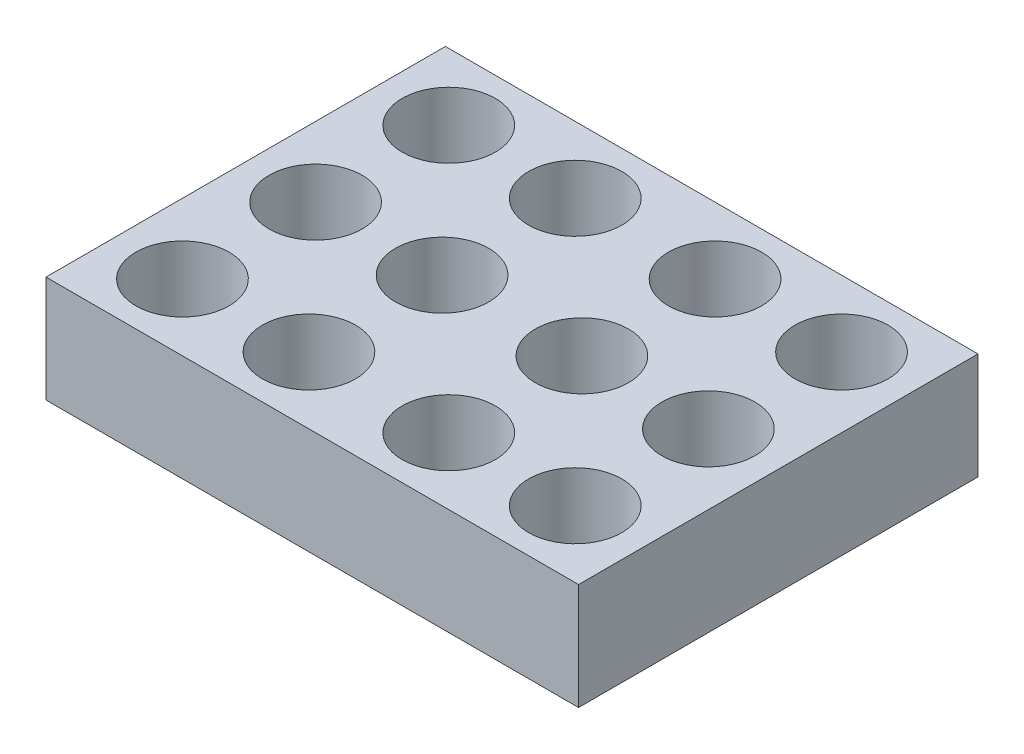
SolidWorks part; units mm, degrees
material "Polietileno reticulado"
ref_plane "Alzado" through (0, 0, 0) normal (0, 0, 1) x (1, 0, 0)
ref_plane "Planta" through (0, 0, 0) normal (0, 1, 0) x (1, 0, 0)
ref_plane "Vista lateral" through (0, 0, 0) normal (1, 0, 0) x (0, 0, -1)
sketch "Croquis1" plane through (0, 0, 0) normal (0, 1, 0) x (1, 0, 0)
  line L1 (-200, -150) -> (200, -150)
  line L2 (-200, -150) -> (-200, 150)
  line L3 (-200, 150) -> (200, 150)
  line L4 (200, -150) -> (200, 150)
  line L5 (-200, -150) -> (200, 150) construction
  line L6 (-200, 150) -> (200, -150) construction
  point P0 (0, 0)
  dimension "D1" = 400
  dimension "D2" = 300
extrude "Saliente-Extruir1" add sketch "Croquis1" along normal blind 80
sketch "Croquis3" plane through (0, 80, 0) normal (0, 1, 0) x (1, 0, 0)
  line L0 (-147.5, 100) -> (-52.5, 100) construction
  line L1 (-182.5, 135) -> (182.5, 135) construction
  line L2 (-182.5, 135) -> (-182.5, -135) construction
  line L3 (-182.5, -135) -> (182.5, -135) construction
  line L4 (182.5, 135) -> (182.5, -135) construction
  line L5 (-182.5, 135) -> (182.5, -135) construction
  line L6 (-182.5, -135) -> (182.5, 135) construction
  line L7 (0, 0) -> (0, 135) construction
  line L8 (-147.5, 100) -> (-147.5, 0) construction
  line L9 (-147.5, 0) -> (-52.5, 0) construction
  line L10 (0, 0) -> (182.5, 0) construction
  line L11 (0, 0) -> (-182.5, 0) construction
  circle A0 centre (-147.5, 100) radius 35
  circle A1 centre (-52.5, 100) radius 35
  circle A2 centre (-147.5, 0) radius 35
  circle A3 centre (-52.5, 0) radius 35
  circle A4 centre (52.5, 0) radius 35
  circle A5 centre (52.5, 100) radius 35
  circle A6 centre (147.5, 0) radius 35
  circle A7 centre (147.5, 100) radius 35
  circle A8 centre (-52.5, -100) radius 35
  circle A9 centre (-147.5, -100) radius 35
  circle A10 centre (147.5, -100) radius 35
  circle A11 centre (52.5, -100) radius 35
  point P0 (0, 0)
  dimension "D1" = 365
  dimension "D2" = 270
extrude "Cortar-Extruir1" cut sketch "Croquis3" against normal blind 70
